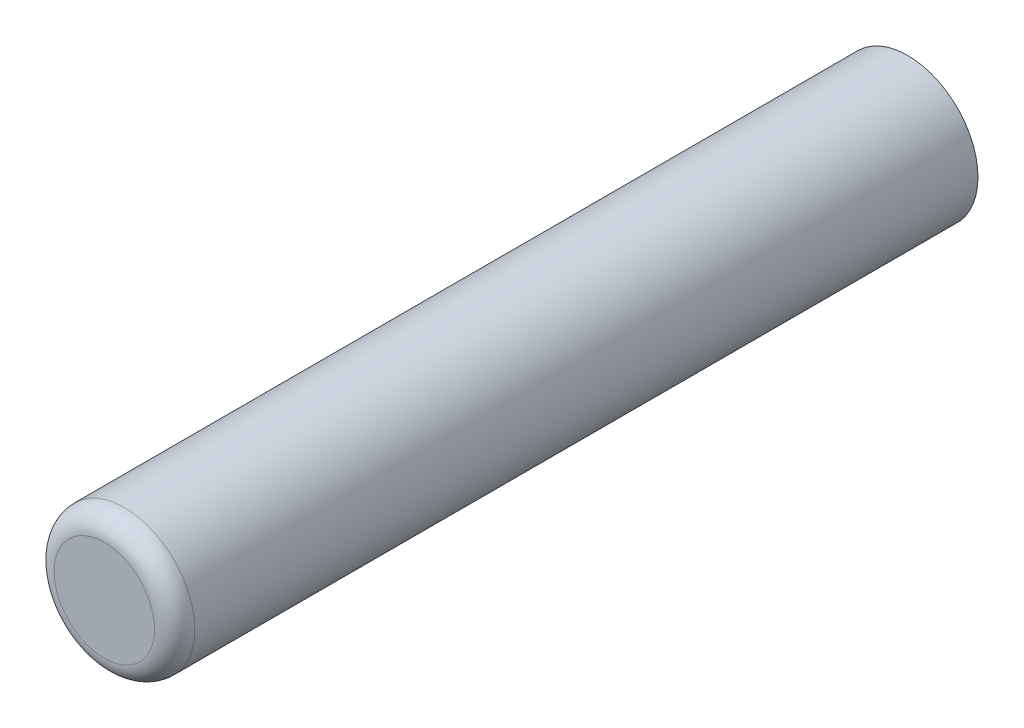
SolidWorks part; units mm, degrees
ref_plane "Plano frontal" through (0, 0, 0) normal (0, 0, 1) x (1, 0, 0)
ref_plane "Plano superior" through (0, 0, 0) normal (0, 1, 0) x (1, 0, 0)
ref_plane "Plano direito" through (0, 0, 0) normal (1, 0, 0) x (0, 0, -1)
sketch "Esboço2" plane through (0, 0, 0) normal (0, 0, 1) x (1, 0, 0)
  line L0 (1.118, 1.25) -> (-1.118, 1.25)
  arc A0 (-1.118, 1.25) -> (1.118, 1.25) centre (0, 0.25) ccw
  circle A2 centre (0, 0.25) radius 1.75
  dimension "D1" = 1.5
extrude "Ressalto-extrusão1" add sketch "Esboço2" along normal blind 9.3
sketch "Esboço3" plane through (0, 0, 9.3) normal (0, 0, 1) x (1, 0, 0)
  circle A0 centre (0, 0.25) radius 1.75
  circle A2 centre (0, 0.25) radius 1.75 construction
  dimension "D1" = 3.5
extrude "Ressalto-extrusão2" add sketch "Esboço3" along normal blind 10.7
fillet "Filete1" radius 0.5 1 edges at (1.75, 0.25, 20)
